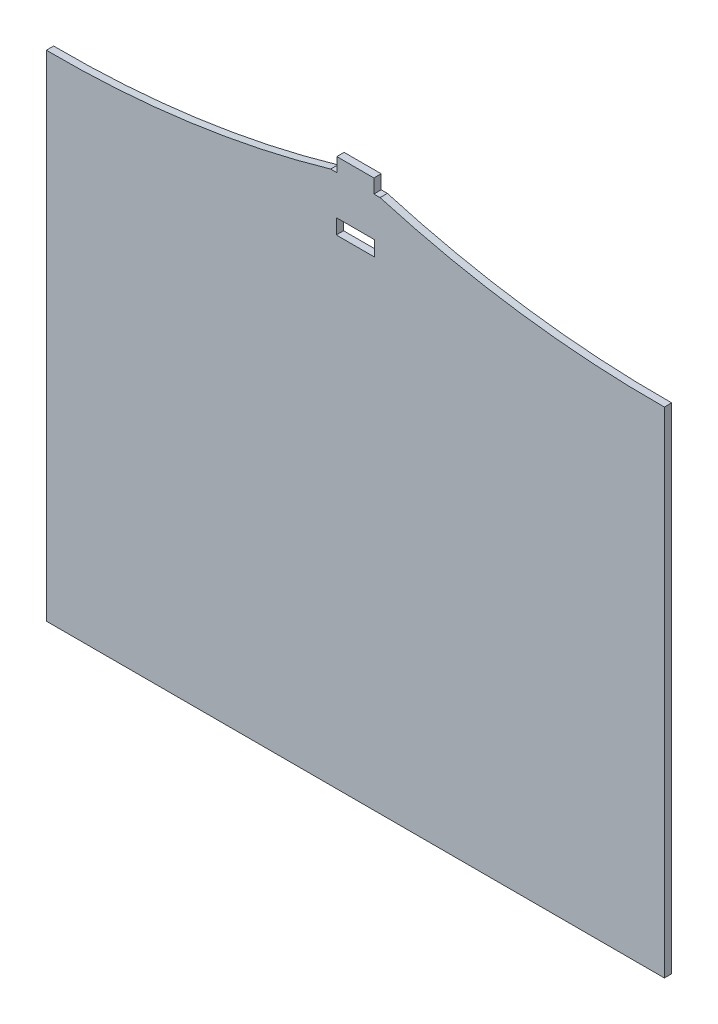
SolidWorks part; units mm, degrees
ref_plane "Front Plane" through (0, 0, 0) normal (0, 0, 1) x (1, 0, 0)
ref_plane "Top Plane" through (0, 0, 0) normal (0, 1, 0) x (1, 0, 0)
ref_plane "Right Plane" through (0, 0, 0) normal (1, 0, 0) x (0, 0, -1)
sketch "Sketch1" plane through (0, 0, 0) normal (0, 0, 1) x (1, 0, 0)
  line L0 (0.1712, 69.4697) -> (2.6712, 69.4697)
  line L2 (-114.8288, 53.5997) -> (-114.8288, -146.4003)
  line L3 (-114.8288, -146.4003) -> (135.1712, -146.4003)
  line L4 (135.1712, 53.5997) -> (135.1712, -146.4003)
  line L5 (17.6712, 69.4697) -> (20.1712, 69.4697)
  line L7 (2.6712, 69.4697) -> (2.6712, 75.0997)
  line L8 (2.6712, 75.0997) -> (17.6712, 75.0997)
  line L9 (17.6712, 69.4697) -> (17.6712, 75.0997)
  line L11 (2.4462, 53.5997) -> (17.8962, 53.5997)
  line L12 (2.4462, 53.5997) -> (2.4462, 47.5197)
  line L13 (2.4462, 47.5197) -> (17.8962, 47.5197)
  line L14 (17.8962, 53.5997) -> (17.8962, 47.5197)
  arc A0 (-114.8288, 53.5997) -> (0.1712, 69.4697) centre (-111.4318, 453.5852) ccw
  arc A1 (20.1712, 69.4697) -> (135.1712, 53.5997) centre (131.7741, 453.5852) ccw
  point P16 (-16.8308, 98.6869)
  point P17 (10.1712, 75.0997)
  point P18 (10.1712, 53.5997)
  point P19 (-79.8122, 242.4987)
  dimension "D11" = 400
  dimension "D12" = 400
  dimension "D1" = 200
  dimension "D2" = 250
  dimension "D4" = 20
  dimension "D3" = 15.87
  dimension "D5" = 5.63
  dimension "D6" = 15
  dimension "D7" = 15.45
  dimension "D8" = 6.08
  dimension "D9" = 125
  dimension "D10" = 10
extrude "Boss-Extrude1" add sketch "Sketch1" along normal blind 2.95
equation "\"Width\"= 250"
equation "\"Height\"= 200"
equation "\"thin Acrylic\"= 2.95"
equation "\"D1@Sketch1\"=\"Height\""
equation "\"D2@Sketch1\"=\"Width\""
equation "\"D1@Boss-Extrude1\"=\"thin Acrylic\""
equation "\"Thick acrylic\"= 5.63"
equation "\"Drone height\"= 21.5"
equation "\"Guard height\"= \"Drone height\" - \"Thick acrylic\""
equation "\"Support width\"= 20"
equation "\"D4@Sketch1\"=\"Support width\""
equation "\"D3@Sketch1\"=\"Guard height\""
equation "\"attach width\"= 15"
equation "\"D5@Sketch1\"=\"Thick acrylic\""
equation "\"D6@Sketch1\"=\"attach width\""
equation "\"gap\" = 0.45"
equation "\"D7@Sketch1\"=\"attach width\"+\"gap\""
equation "\"D8@Sketch1\"=\"Thick acrylic\"+\"gap\""
equation "\"D9@Sketch1\"=\"Width\"/2"
equation "\"D10@Sketch1\"=\"Support width\"/2"
